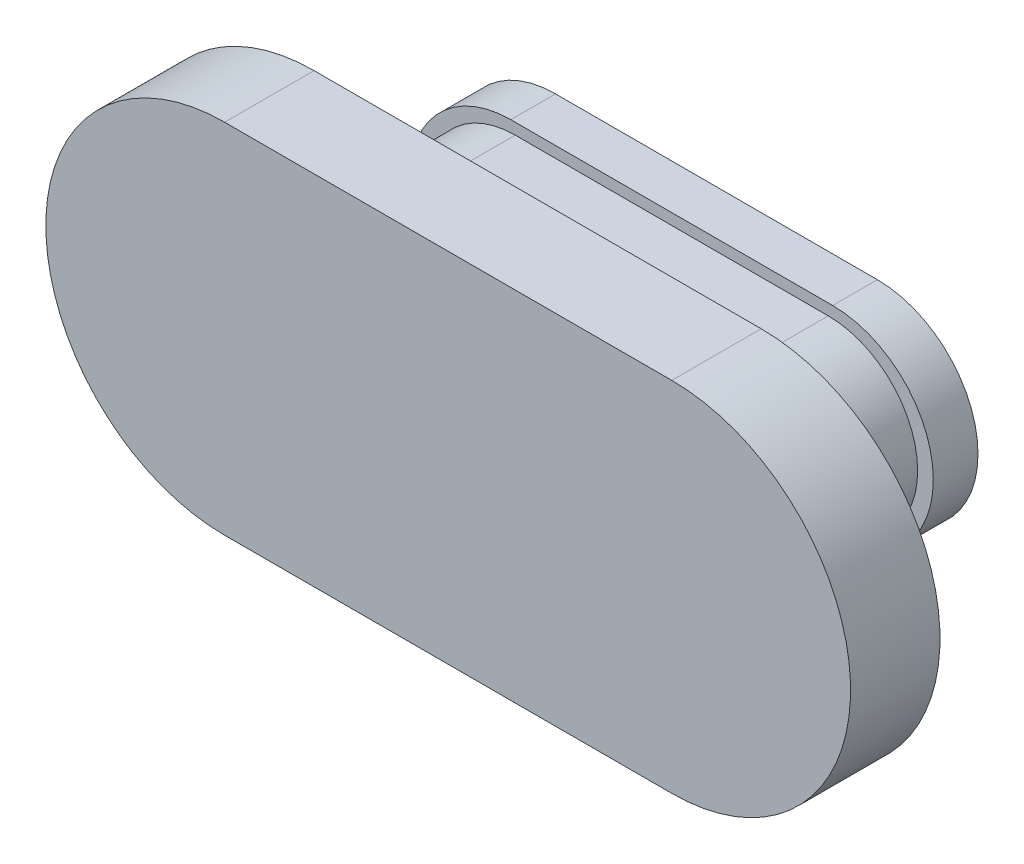
SolidWorks part; units mm, degrees
ref_plane "Plan de face" through (0, 0, 0) normal (0, 0, 1) x (1, 0, 0)
ref_plane "Plan de dessus" through (0, 0, 0) normal (0, 1, 0) x (1, 0, 0)
ref_plane "Plan de droite" through (0, 0, 0) normal (1, 0, 0) x (0, 0, -1)
sketch "Esquisse1" plane through (0, 0, 0) normal (0, 0, 1) x (1, 0, 0)
  line L0 (-3.5, 0) -> (3.5, 0) construction
  line L1 (-3.5, 2) -> (3.5, 2)
  line L2 (-3.5, -2) -> (3.5, -2)
  arc A0 (-3.5, 2) -> (-3.5, -2) centre (-3.5, 0) ccw
  arc A1 (3.5, -2) -> (3.5, 2) centre (3.5, 0) ccw
  point P2 (0, 0)
  dimension "D1" = 7
  dimension "D2" = 4
extrude "Boss.-Extru.1" add sketch "Esquisse1" along normal mid plane 3
sketch "Esquisse2" plane through (0, 0, 0) normal (0, 0, 1) x (1, 0, 0)
  line L0 (-5, 0) -> (5, 0) construction
  line L1 (-5, 4) -> (5, 4)
  line L2 (-5, -4) -> (5, -4)
  arc A0 (-5, 4) -> (-5, -4) centre (-5, 0) ccw
  arc A1 (5, -4) -> (5, 4) centre (5, 0) ccw
  point P2 (0, 0)
  dimension "D1" = 10
  dimension "D2" = 8
extrude "Boss.-Extru.2" add sketch "Esquisse2" along normal blind 2 from surface at 1.5 contours A0 L2 A1 L1 starting at face at (0, 0, 1.5)
sketch "Esquisse3" plane through (0, 0, -1.5) normal (0, 0, -1) x (-1, 0, 0)
  line L0 (-3.6, 0) -> (3.6, 0) construction
  line L1 (-3.6, 2.25) -> (3.6, 2.25)
  line L2 (-3.6, -2.25) -> (3.6, -2.25)
  arc A0 (-3.6, 2.25) -> (-3.6, -2.25) centre (-3.6, 0) ccw
  arc A1 (3.6, -2.25) -> (3.6, 2.25) centre (3.6, 0) ccw
  point P2 (0, 0)
  dimension "D1" = 7.2
  dimension "D2" = 4.5
extrude "Boss.-Extru.3" add sketch "Esquisse3" along normal blind 1
